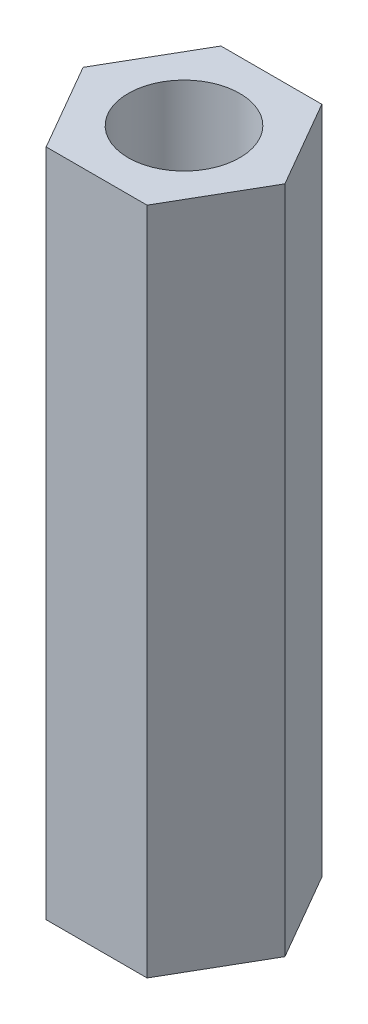
SolidWorks part; units mm, degrees
material "黄铜"
ref_plane "前视基准面" through (0, 0, 0) normal (0, 0, 1) x (1, 0, 0)
ref_plane "上视基准面" through (0, 0, 0) normal (0, 1, 0) x (1, 0, 0)
ref_plane "右视基准面" through (0, 0, 0) normal (1, 0, 0) x (0, 0, -1)
other "Configuration Table"
sketch "草图1" plane through (0, 0, 0) normal (0, 1, 0) x (1, 0, 0)
  line L0 (-2.7135, 0) -> (2.7135, 0) construction
  line L1 (1.3568, -2.35) -> (2.7135, 0)
  line L2 (2.7135, 0) -> (1.3568, 2.35)
  line L3 (1.3568, 2.35) -> (-1.3568, 2.35)
  line L4 (-1.3568, 2.35) -> (-2.7135, 0)
  line L5 (-2.7135, 0) -> (-1.3568, -2.35)
  line L6 (-1.3568, -2.35) -> (1.3568, -2.35)
  circle A0 centre (0, 0) radius 2.35 construction
  circle A1 centre (0, 0) radius 1.5
  point P13 (0, 0)
  dimension "D2" = 3
  dimension "D1" = 4.7
extrude "凸台-拉伸1" add sketch "草图1" along normal blind 18
